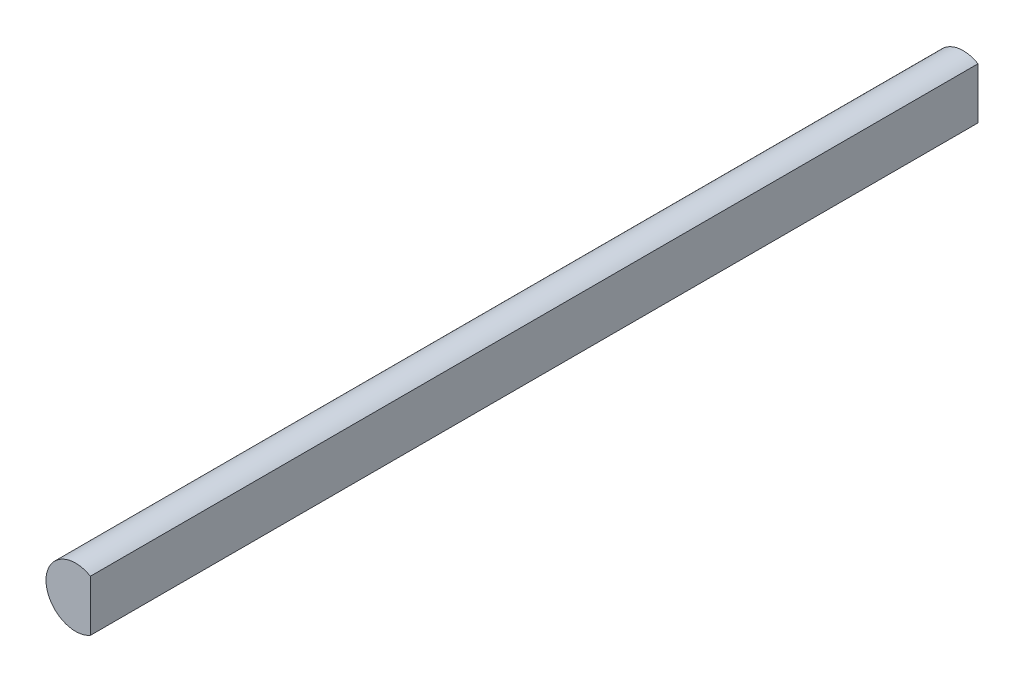
SolidWorks part; units mm, degrees
ref_plane "前视基准面" through (0, 0, 0) normal (0, 0, 1) x (1, 0, 0)
ref_plane "上视基准面" through (0, 0, 0) normal (0, 1, 0) x (1, 0, 0)
ref_plane "右视基准面" through (0, 0, 0) normal (1, 0, 0) x (0, 0, -1)
sketch "草图1" plane through (0, 0, 0) normal (0, 0, 1) x (1, 0, 0)
  line L0 (1, 1.7321) -> (1, -1.7321)
  arc A0 (1, 1.7321) -> (1, -1.7321) centre (0, 0) ccw
  dimension "D2" = 2
  dimension "D1" = 1
extrude "凸台-拉伸1" add sketch "草图1" along normal mid plane 60
